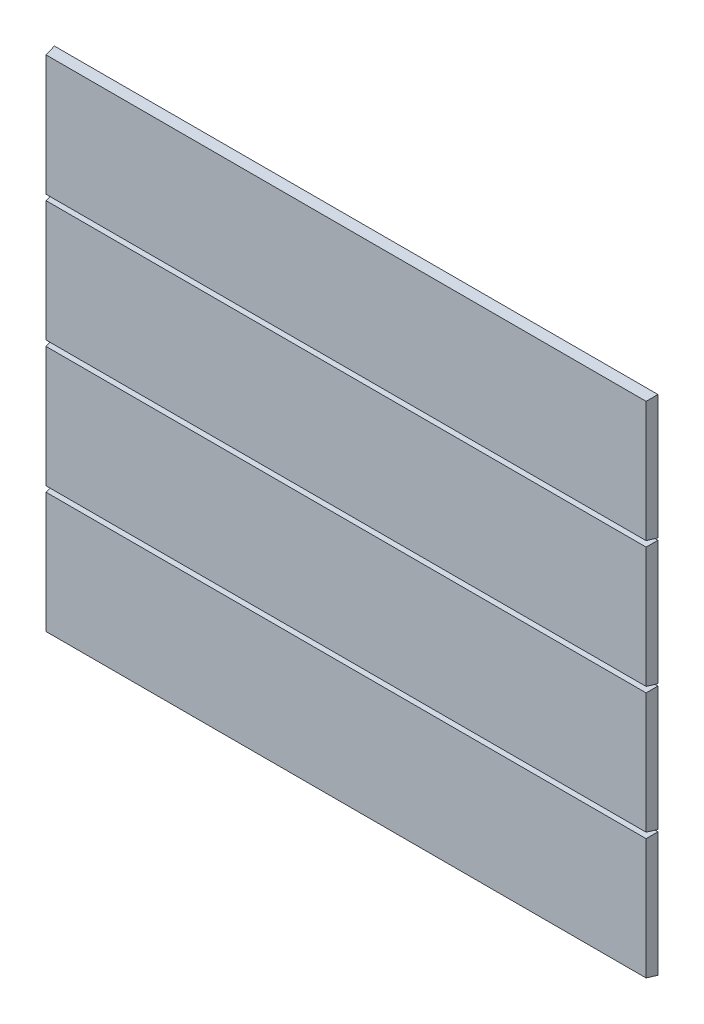
SolidWorks part; units mm, degrees
ref_plane "Спереди" through (0, 0, 0) normal (0, 0, 1) x (1, 0, 0)
ref_plane "Сверху" through (0, 0, 0) normal (0, 1, 0) x (1, 0, 0)
ref_plane "Справа" through (0, 0, 0) normal (1, 0, 0) x (0, 0, -1)
other "Configuration Table"
sketch "Эскиз1" plane through (0, 0, 0) normal (0, 0, 1) x (1, 0, 0)
  line L0 (0, -123.4554) -> (0, 0) construction
  line L1 (-1500, -123.4554) -> (1500, -123.4554)
  line L2 (-1500, -123.4554) -> (-1500, -740.9554)
  line L3 (-1500, -740.9554) -> (1500, -740.9554)
  line L4 (1500, -123.4554) -> (1500, -740.9554)
  line L5 (-1500, -750.9554) -> (1500, -750.9554)
  line L6 (-1500, -750.9554) -> (-1500, -1368.4554)
  line L7 (-1500, -1368.4554) -> (1500, -1368.4554)
  line L8 (1500, -750.9554) -> (1500, -1368.4554)
  line L9 (-1500, -1378.4554) -> (1500, -1378.4554)
  line L10 (-1500, -1378.4554) -> (-1500, -1995.9554)
  line L11 (-1500, -1995.9554) -> (1500, -1995.9554)
  line L12 (1500, -1378.4554) -> (1500, -1995.9554)
  line L13 (-1500, -2005.9554) -> (1500, -2005.9554)
  line L14 (-1500, -2005.9554) -> (-1500, -2623.4554)
  line L15 (-1500, -2623.4554) -> (1500, -2623.4554)
  line L16 (1500, -2005.9554) -> (1500, -2623.4554)
  point P18 (0, 0)
  dimension "D1" = 3000
  dimension "D2" = 10
  dimension "D3" = 10
  dimension "D4" = 10
  dimension "D5" = 2500
extrude "Бобышка-Вытянуть1" add sketch "Эскиз1" along normal blind 50 draft 10
